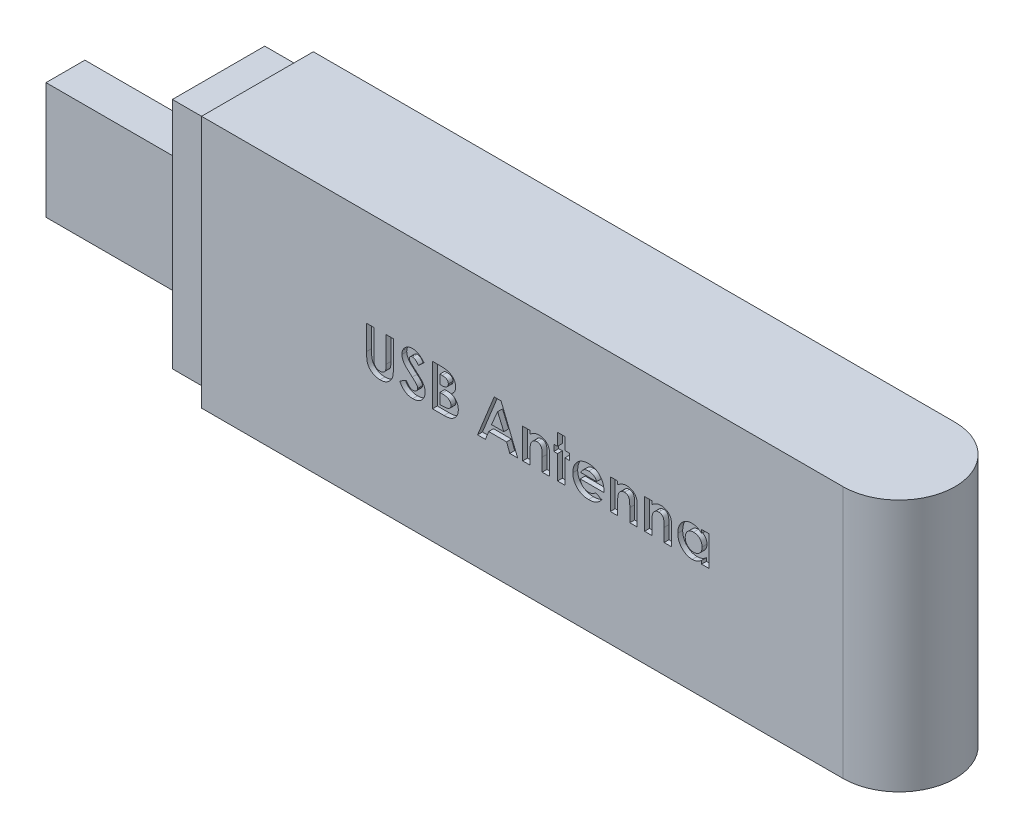
SolidWorks part; units mm, degrees
ref_plane "Front Plane" through (0, 0, 0) normal (0, 0, 1) x (1, 0, 0)
ref_plane "Top Plane" through (0, 0, 0) normal (0, 1, 0) x (1, 0, 0)
ref_plane "Right Plane" through (0, 0, 0) normal (1, 0, 0) x (0, 0, -1)
sketch "Sketch1" plane through (0, 0, 0) normal (0, 1, 0) x (1, 0, 0)
  line L1 (0, 0) -> (70, 0)
  line L2 (0, 0) -> (0, 11.5)
  line L3 (0, 11.5) -> (70, 11.5)
  line L4 (70, 0) -> (70, 11.5)
  arc A0 (70, 0) -> (70, 11.5) centre (70, 5.75) ccw
  dimension "D1" = 11.5
  dimension "D2" = 70
extrude "Boss-Extrude1" add sketch "Sketch1" along normal blind 26 contours L1 L4 L3 L2 | L4 A0
sketch "Sketch2" plane through (0, 0, 0) normal (-1, 0, 0) x (0, 0, 1)
  line L0 (0, 26) -> (0, 0) construction
  line L1 (-10.5, 25) -> (-1, 25)
  line L2 (-10.5, 25) -> (-10.5, 1)
  line L3 (-10.5, 1) -> (-1, 1)
  line L4 (-1, 25) -> (-1, 1)
  line L5 (-11.5, 26) -> (-11.5, 0) construction
  line L6 (0, 26) -> (-11.5, 26) construction
  line L7 (0, 0) -> (-11.5, 0) construction
  line L12 (-11.5, 0) -> (0, 0)
  line L13 (0, 0) -> (0, 26)
  line L14 (0, 26) -> (-11.5, 26)
  line L15 (-11.5, 26) -> (-11.5, 0)
  line L16 (-11.5, 0) -> (0, 0)
  line L17 (0, 0) -> (0, 26)
  line L18 (0, 26) -> (-11.5, 26)
  line L19 (-11.5, 26) -> (-11.5, 0)
  dimension "D1" = 1
  dimension "D2" = 1
  dimension "D3" = 1
  dimension "D4" = 1
  dimension "D5" = 0
extrude "Cut-Extrude1" cut sketch "Sketch2" against normal blind 4
sketch "Sketch3" plane through (0, 0, 0) normal (-1, 0, 0) x (0, 0, 1)
  line L0 (-1, 1) -> (-1, 25) construction
  line L1 (-6, 19) -> (-2, 19)
  line L2 (-6, 19) -> (-6, 7)
  line L3 (-6, 7) -> (-2, 7)
  line L4 (-2, 19) -> (-2, 7)
  line L5 (-10.5, 1) -> (-1, 1) construction
  dimension "D1" = 4
  dimension "D2" = 12
  dimension "D3" = 1
  dimension "D4" = 6
extrude "Boss-Extrude2" add sketch "Sketch3" along normal blind 14
sketch "Sketch6" plane through (0, 0, 0) normal (0, 0, 1) x (1, 0, 0)
  text T0 "<b>USB Antenna</b>" font "Century Gothic" height in points 16
extrude "Cut-Extrude3" cut sketch "Sketch6" against normal blind 0.5
